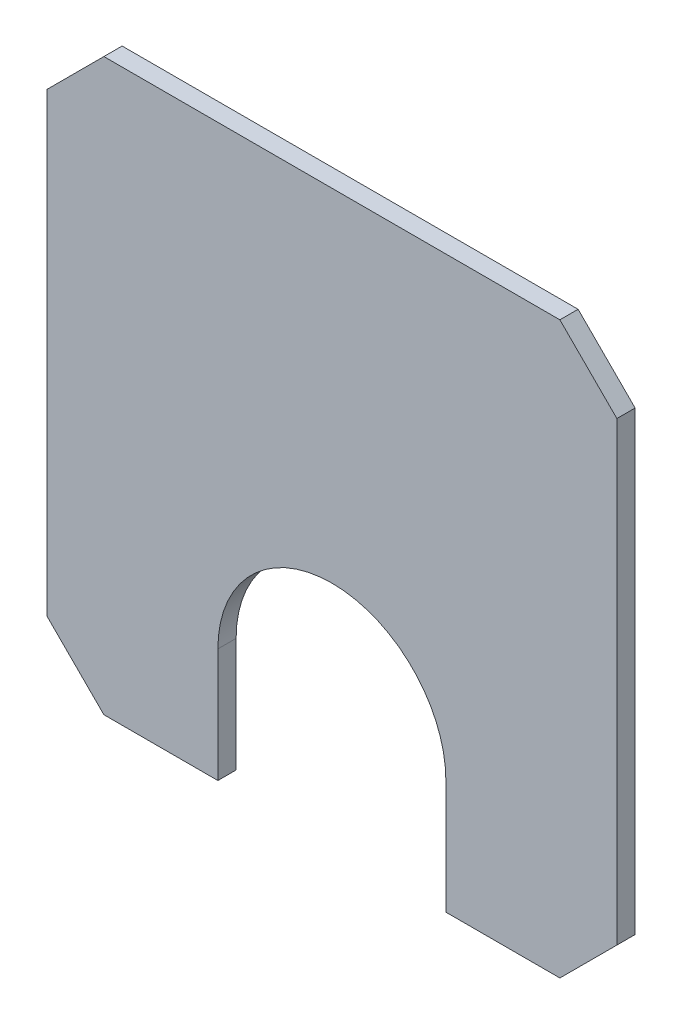
SolidWorks part; units mm, degrees
ref_plane "前基準面" through (0, 0, 0) normal (0, 0, 1) x (1, 0, 0)
ref_plane "上基準面" through (0, 0, 0) normal (0, 1, 0) x (1, 0, 0)
ref_plane "右基準面" through (0, 0, 0) normal (1, 0, 0) x (0, 0, -1)
sketch "草圖1" plane through (0, 0, 0) normal (0, 0, 1) x (1, 0, 0)
  line L11 (15, 10) -> (15, 0)
  line L12 (15, 0) -> (5, 0)
  line L13 (5, 0) -> (0, 5)
  line L14 (0, 5) -> (0, 45)
  line L15 (0, 45) -> (5, 50)
  line L16 (5, 50) -> (45, 50)
  line L17 (45, 50) -> (50, 45)
  line L18 (50, 45) -> (50, 5)
  line L19 (50, 5) -> (45, 0)
  line L20 (45, 0) -> (35, 0)
  line L21 (35, 0) -> (35, 10)
  arc A1 (35, 10) -> (15, 10) centre (25, 10) ccw
extrude "Board" add sketch "草圖1" along normal blind 1.6
